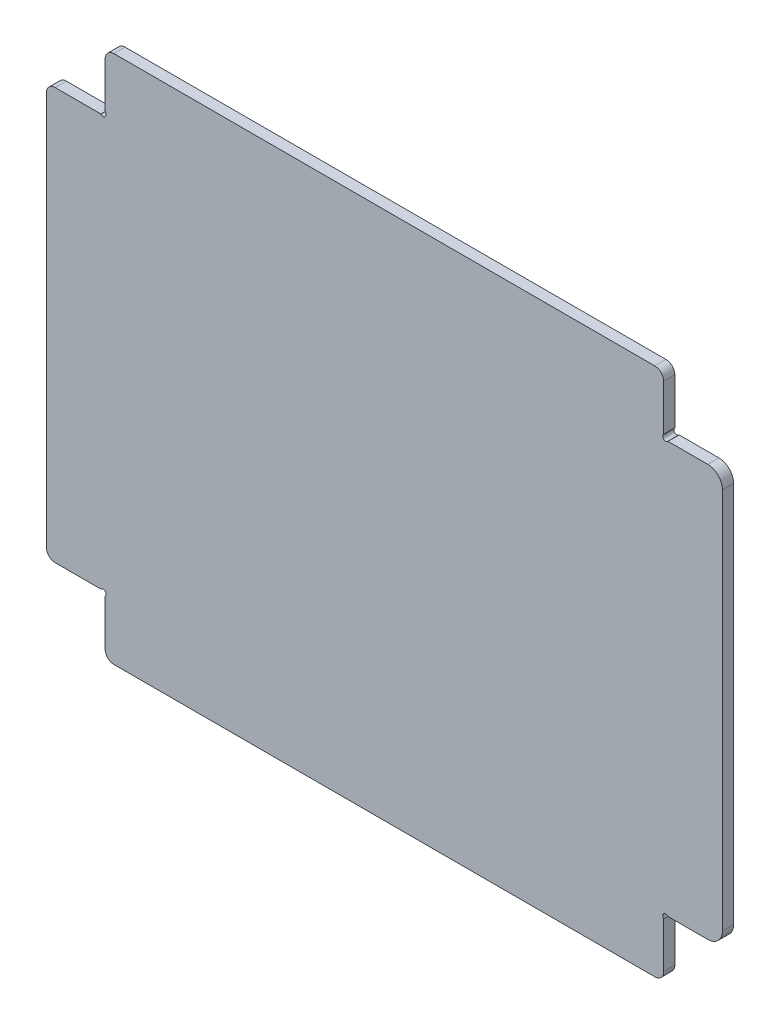
SolidWorks part; units mm, degrees
ref_plane "Front Plane" through (0, 0, 0) normal (0, 0, 1) x (1, 0, 0)
ref_plane "Top Plane" through (0, 0, 0) normal (0, 1, 0) x (1, 0, 0)
ref_plane "Right Plane" through (0, 0, 0) normal (1, 0, 0) x (0, 0, -1)
sketch "Sketch1" plane through (0, 0, 0) normal (0, 0, 1) x (1, 0, 0)
  line L1 (-138.7521, 112.3539) -> (45.2479, 112.3539)
  line L2 (-161.7521, 89.3539) -> (-161.7521, -44.6461)
  line L3 (-138.7521, -67.6461) -> (45.2479, -67.6461)
  line L6 (48.2479, 109.3539) -> (48.2479, 93.7112)
  line L8 (63.2479, 92.3539) -> (49.7123, 92.3539)
  line L10 (118.2479, 22.3539) -> (33.8619, 22.3539) construction
  line L11 (-46.7521, 105.8539) -> (-46.7521, 74.5738) construction
  line L12 (63.2479, -47.6461) -> (49.7123, -47.6461)
  line L13 (48.2479, -64.6461) -> (48.2479, -49.0034)
  line L14 (-141.7521, -64.6461) -> (-141.7521, -49.0034)
  line L15 (-158.7521, -47.6461) -> (-143.2166, -47.6461)
  line L16 (-158.7521, 92.3539) -> (-143.2166, 92.3539)
  line L17 (-141.7521, 109.3539) -> (-141.7521, 93.7112)
  line L26 (68.2479, 87.3539) -> (68.2479, -42.6461)
  arc A0 (-141.7521, -64.6461) -> (-138.7521, -67.6461) centre (-138.7521, -64.6461) ccw
  arc A1 (-158.7521, -47.6461) -> (-161.7521, -44.6461) centre (-158.7521, -44.6461) cw
  arc A2 (-158.7521, 92.3539) -> (-161.7521, 89.3539) centre (-158.7521, 89.3539) ccw
  arc A3 (-141.7521, 109.3539) -> (-138.7521, 112.3539) centre (-138.7521, 109.3539) cw
  arc A4 (48.2479, 109.3539) -> (45.2479, 112.3539) centre (45.2479, 109.3539) ccw
  arc A7 (48.2479, -64.6461) -> (45.2479, -67.6461) centre (45.2479, -64.6461) cw
  arc A11 (-143.2166, 92.3539) -> (-141.7521, 93.7112) centre (-142.4454, 92.9906) ccw
  arc A12 (49.7123, 92.3539) -> (48.2479, 93.7112) centre (48.9412, 92.9906) cw
  arc A13 (49.7123, -47.6461) -> (48.2479, -49.0034) centre (48.9412, -48.2827) ccw
  arc A14 (-143.2166, -47.6461) -> (-141.7521, -49.0034) centre (-142.4454, -48.2827) cw
  arc A17 (68.2479, 87.3539) -> (63.2479, 92.3539) centre (63.2479, 87.3539) ccw
  arc A18 (68.2479, -42.6461) -> (63.2479, -47.6461) centre (63.2479, -42.6461) cw
  point P3 (-141.7521, -67.6461)
  point P11 (68.2479, 92.3539)
  point P14 (68.2479, -47.6461)
  point P26 (-161.7521, -47.6461)
  point P29 (-161.7521, 92.3539)
  point P32 (-141.7521, 112.3539)
  point P35 (48.2479, 112.3539)
  point P38 (68.2479, 92.3539)
  point P39 (118.2479, -47.6461)
  point P40 (68.2479, -47.6461)
  point P43 (48.2479, -67.6461)
  point P50 (118.2479, 92.3539)
  dimension "D1" = 3
  dimension "D2" = 5
  dimension "D6" = 2
extrude "Boss-Extrude1" add sketch "Sketch1" along normal blind 3.8
